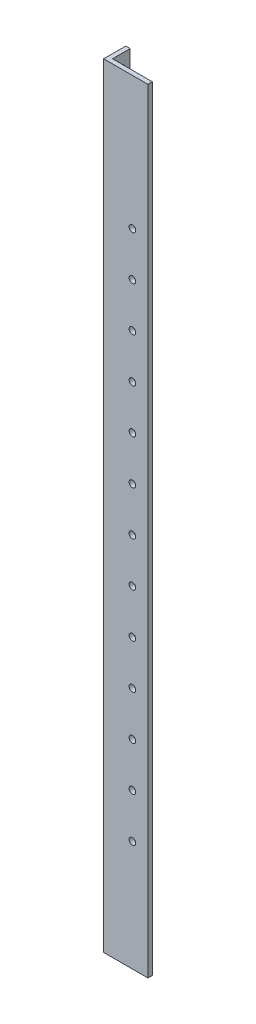
SolidWorks part; units mm, degrees
ref_plane "Front Plane" through (0, 0, 0) normal (0, 0, 1) x (1, 0, 0)
ref_plane "Top Plane" through (0, 0, 0) normal (0, 1, 0) x (1, 0, 0)
ref_plane "Right Plane" through (0, 0, 0) normal (1, 0, 0) x (0, 0, -1)
sketch "Sketch1" plane through (0, 0, 0) normal (0, 1, 0) x (1, 0, 0)
  line L0 (0, 0) -> (0, 10)
  line L1 (0, 10) -> (2, 10)
  line L2 (2, 10) -> (2, 2)
  line L3 (2, 2) -> (20, 2)
  line L4 (20, 2) -> (20, 0)
  line L5 (20, 0) -> (0, 0)
extrude "Boss-Extrude1" add sketch "Sketch1" along normal blind 350
hole_wizard "Ø3.0 (3) Diameter Hole1" positions "Sketch2" profile "Sketch3" hole size "Ø3.0" standard "ISO" end condition through all
sketch "Sketch2" plane through (2, -11.4076, -188.68) normal (1, 0, 0) x (0, 0, -1)
  point P0 (-182.68, 17.4076)
  point P1 (-182.68, 31.4076)
sketch "Sketch3" plane through (2, 6, -6) normal (0, 1, 0) x (0, 0, -1)
  line L0 (0, 0) -> (0, 2)
  line L1 (0, 2) -> (1.5, 2)
  line L2 (1.5, 2) -> (1.5, 0)
  line L3 (1.5, 0) -> (0, 0)
  line L4 (0, -6.35) -> (0, 107.95) construction
  dimension "Thru Hole Dia." = 3
  dimension "Thru Hole Depth" = 2
hole_wizard "Ø3.0 (3) Diameter Hole2" positions "Sketch4" profile "Sketch5" hole size "Ø3.0" standard "ISO" end condition through all
sketch "Sketch4" plane through (2, -11.4076, -188.68) normal (1, 0, 0) x (0, 0, -1)
  point P0 (-182.68, 355.4076)
  point P1 (-182.68, 341.4076)
sketch "Sketch5" plane through (2, 344, -6) normal (0, 1, 0) x (0, 0, -1)
  line L0 (0, 0) -> (0, 2)
  line L1 (0, 2) -> (1.5, 2)
  line L2 (1.5, 2) -> (1.5, 0)
  line L3 (1.5, 0) -> (0, 0)
  line L4 (0, -6.35) -> (0, 107.95) construction
  dimension "Thru Hole Dia." = 3
  dimension "Thru Hole Depth" = 2
sketch "Sketch6" plane through (0, 0, 0) normal (0, 0, 1) x (1, 0, 0)
  circle A0 centre (13, 290) radius 1.5
  circle A1 centre (13, 270) radius 1.5
  circle A2 centre (13, 250) radius 1.5
  circle A3 centre (13, 230) radius 1.5
  circle A4 centre (13, 210) radius 1.5
  circle A5 centre (13, 190) radius 1.5
  circle A6 centre (13, 170) radius 1.5
  circle A7 centre (13, 150) radius 1.5
  circle A8 centre (13, 130) radius 1.5
  circle A9 centre (13, 110) radius 1.5
  circle A10 centre (13, 90) radius 1.5
  circle A11 centre (13, 70) radius 1.5
  circle A12 centre (13, 50) radius 1.5
  point P40 (0, 0)
extrude "Cut-Extrude1" cut sketch "Sketch6" against normal through all
